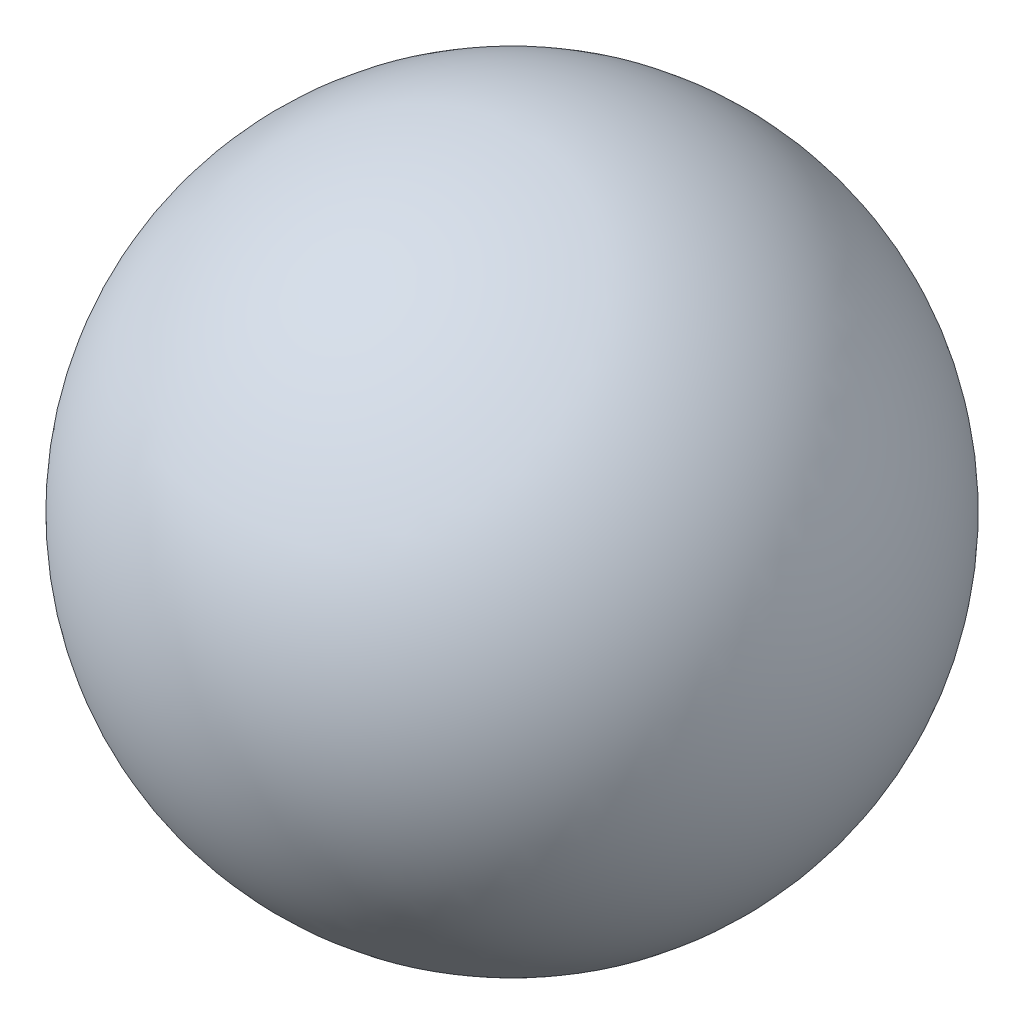
SolidWorks part; units mm, degrees
ref_plane "Front Plane" through (0, 0, 0) normal (0, 0, 1) x (1, 0, 0)
ref_plane "Top Plane" through (0, 0, 0) normal (0, 1, 0) x (1, 0, 0)
ref_plane "Right Plane" through (0, 0, 0) normal (1, 0, 0) x (0, 0, -1)
sketch "Sketch1" plane through (0, 0, 0) normal (0, 0, 1) x (1, 0, 0)
  line L0 (0, 6.8199) -> (0, -6.8199)
  arc A0 (0, 6.8199) -> (0, -6.8199) centre (0, 0) cw
  dimension "D1" = 6.8199
revolve "Revolve1" add sketch "Sketch1" angle 360 about L0
